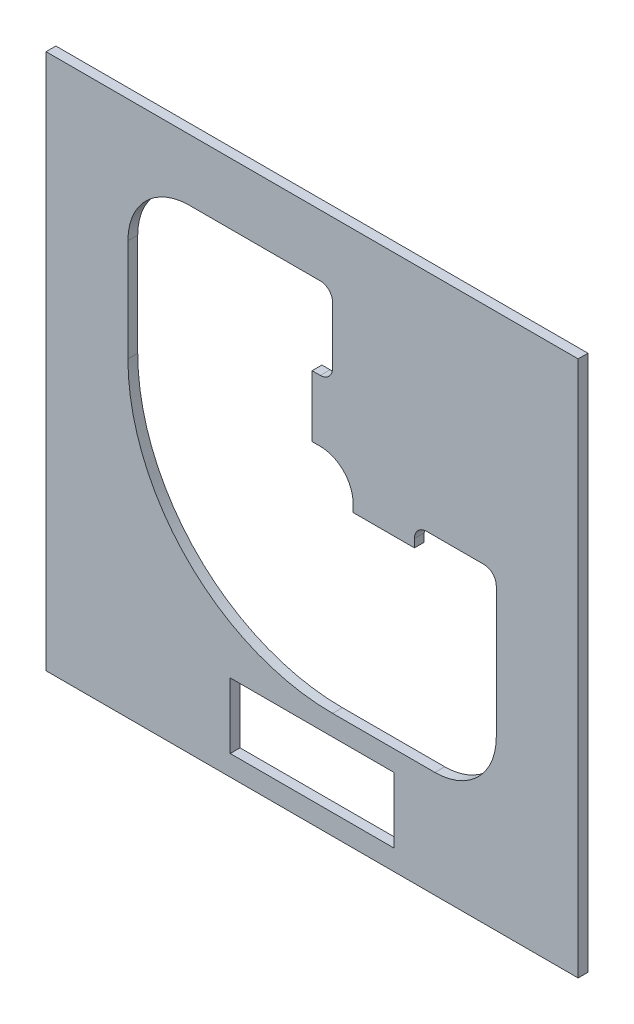
SolidWorks part; units mm, degrees
material "PBT General Purpose"
ref_plane "Front Plane" through (0, 0, 0) normal (0, 0, 1) x (1, 0, 0)
ref_plane "Top Plane" through (0, 0, 0) normal (0, 1, 0) x (1, 0, 0)
ref_plane "Right Plane" through (0, 0, 0) normal (1, 0, 0) x (0, 0, -1)
sketch "Sketch1" plane through (0, 0, 0) normal (0, 0, 1) x (1, 0, 0)
  line L0 (-1, 0.5) -> (-1, 5.5)
  line L1 (0, 0) -> (-11, 0)
  line L2 (0, 0) -> (0, 10.5)
  line L3 (0, 10.5) -> (-11, 10.5) construction
  line L4 (-11, 0) -> (-11, 10.5)
  line L5 (-3, 5.5) -> (-1, 5.5)
  line L6 (-3, 5.5) -> (-3, 5)
  line L7 (-3, 5) -> (-4.5, 5)
  line L8 (-4.5, 5) -> (-4.5, 6)
  line L9 (-4.5, 6) -> (-5.5, 6)
  line L10 (-5.5, 6) -> (-5.5, 7.5)
  line L11 (-5.5, 7.5) -> (-5, 7.5)
  line L12 (-5, 7.5) -> (-5, 9.5)
  line L13 (-5, 9.5) -> (-10, 9.5)
  line L14 (-1, 0.5) -> (-10, 0.5)
  line L15 (-10, 0.5) -> (-10, 9.5)
  line L18 (-11, 10.5) -> (-11, 11)
  line L19 (-11, 11) -> (0, 11)
  line L20 (0, 10.5) -> (0, 11)
  dimension "D1" = 10.5
  dimension "D2" = 11
  dimension "D3" = 1
  dimension "D4" = 0.5
  dimension "1" = 1
  dimension "D5" = 5
  dimension "D6" = 5
  dimension "D7" = 1
  dimension "D8" = 2
  dimension "D9" = 1.5
  dimension "D10" = 1.5
  dimension "D11" = 0.5
  dimension "D12" = 0.5
  dimension "D13" = 2
  dimension "D14" = 0.5
extrude "Boss-Extrude1" add sketch "Sketch1" along normal mid plane 0.24
fillet "Fillet2" radius 1.5 2 edges at (-10, 9.5, 0) (-1, 0.5, 0)
fillet "Fillet3" radius 5 1 edges at (-10, 0.5, 0)
sketch "Sketch4" plane through (0, 0, 0) normal (0, 0, 1) x (1, 0, 0)
  line L0 (0, 0) -> (0, -2.1)
  line L2 (-3.5, -1.6) -> (-3.5, 0)
  line L3 (-11, 0) -> (0, 0) construction
  line L4 (-11, 0) -> (0, 0) construction
  line L5 (-7.5, 0) -> (-7.5, -1.6)
  line L7 (-11, -2.1) -> (-11, 0)
  line L8 (-11, 0) -> (-7.5, 0)
  line L9 (-3.5, 0) -> (0, 0)
  line L11 (-3.5, -1.6) -> (-7.5, -1.6)
  line L13 (0, -2.1) -> (-11, -2.1)
  point P16 (-5.5, 0)
  point P17 (-5.5, -1.6)
  dimension "D1" = 4
  dimension "D2" = 1.6
  dimension "D3" = 0.5
extrude "Boss-Extrude2" add sketch "Sketch4" along normal mid plane 0.24
sketch "Sketch5" plane through (0, 0, 0) normal (0, 0, 1) x (1, 0, 0)
  line L0 (0, 11) -> (-11, 11) construction
  line L1 (-11, 11) -> (-12, 11)
  line L2 (-11, 11) -> (-11, -2.1)
  line L3 (-11, -2.1) -> (-12, -2.1)
  line L4 (-12, 11) -> (-12, -2.1)
  line L5 (0, -2.1) -> (1, -2.1)
  line L6 (0, -2.1) -> (0, 11)
  line L7 (0, 11) -> (1, 11)
  line L8 (1, -2.1) -> (1, 11)
  line L13 (-3.4404, 9.7665) -> (-0.5174, 9.7665)
  line L14 (-3.4404, 9.7665) -> (-3.4404, 6.9479)
  line L15 (-3.4404, 6.9479) -> (-0.5174, 6.9479)
  line L16 (-0.5174, 9.7665) -> (-0.5174, 6.9479)
  dimension "D1" = 1
  dimension "D2" = 1
extrude "Boss-Extrude3" add sketch "Sketch5" along normal mid plane 0.24
fillet "Fillet5" radius 0.3 4 edges at (-1, 5.5, 0) (-3, 5.5, 0) (-5, 7.5, 0) (-5, 9.5, 0)
fillet "Fillet6" radius 0.8 1 edges at (-4.5, 6, 0)
